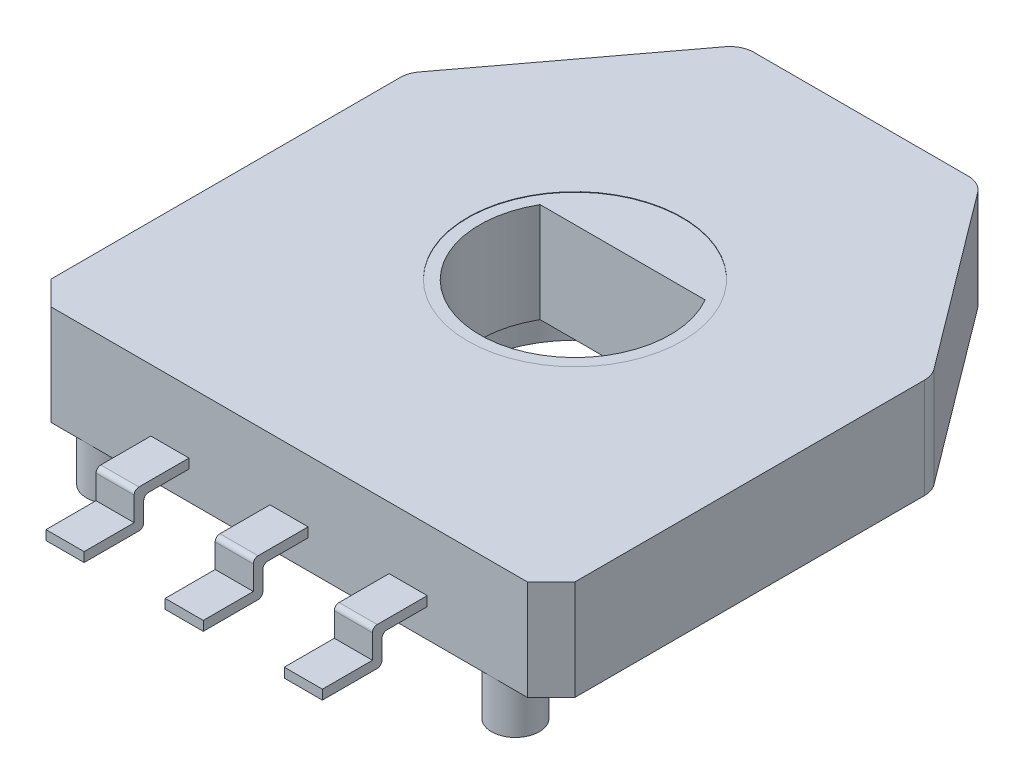
SolidWorks part; units mm, degrees
ref_plane "Front Plane" through (0, 0, 0) normal (0, 0, 1) x (1, 0, 0)
ref_plane "Top Plane" through (0, 0, 0) normal (0, 1, 0) x (1, 0, 0)
ref_plane "Right Plane" through (0, 0, 0) normal (1, 0, 0) x (0, 0, -1)
sketch "Sketch1" plane through (0, 0, 0) normal (0, 1, 0) x (1, 0, 0)
  line L0 (-1005.5, 0) -> (48994.5, 0) construction
  line L1 (5.5, -6) -> (-5.5, -6)
  line L2 (5.5, -6) -> (5.5, 6)
  line L3 (5.5, 6) -> (-5.5, 6)
  line L4 (-5.5, -6) -> (-5.5, 6)
  line L5 (5.5, -6) -> (-5.5, 6) construction
  line L6 (5.5, 6) -> (-5.5, -6) construction
  line L7 (0, -994) -> (0, 49006) construction
  line L8 (-1.7321, 1) -> (1.7321, 1)
  line L9 (-1005.5, 1) -> (48994.5, 1) construction
  line L10 (-1012.2378, 2) -> (48987.7622, 2) construction
  line L11 (2.5, -994) -> (2.5, 49006) construction
  line L12 (-2.5, -994) -> (-2.5, 49006) construction
  line L13 (-5.5, 2) -> (-2.5, 6)
  line L14 (2.5, 6) -> (5.5, 2)
  line L15 (-1005.5, -5.5) -> (48994.5, -5.5) construction
  line L16 (-5.5, -5.5) -> (-5, -6)
  line L17 (5.5, -5.5) -> (5, -6)
  arc A0 (-1.7321, 1) -> (1.7321, 1) centre (0, 0) ccw
  circle A1 centre (0, 0) radius 2.5
  point P0 (0, 0)
  point P9 (-5.5, 0)
  point P12 (0, 6)
  dimension "D3" = 4
  dimension "D5" = 5
  dimension "D1" = 11
  dimension "D2" = 12
  dimension "D6" = 2
  dimension "D10" = 0.5
  dimension "D4" = 1
  dimension "D7" = 2.5
  dimension "D8" = 2.5
  dimension "D9" = 5.5
extrude "FormaBase" add sketch "Sketch1" along normal blind 2.1 contours L17 L2 L14 L3 L13 L4 L16 L1 A1 | A1 A0 L8
fillet "Fillet1" radius 0.5 4 edges at (-2.5, 1.05, -6) (2.5, 1.05, -6) (5.5, 1.05, -2) (-5.5, 1.05, -2)
sketch "Sketch2" plane through (5.5, 0, 0) normal (1, 0, 0) x (0, 0, -1)
  line L0 (-1000, 0) -> (0, 0) construction
  line L1 (0, -1000) -> (0, 49000) construction
  line L2 (-7.05, 0) -> (-8.2, 0)
  line L3 (-6, 0) -> (-6, 0.8)
  line L4 (-6, 0.8) -> (-7.05, 0.8)
  line L5 (-8.2, 0) -> (-8.2, 0.2)
  line L6 (-6.85, 0.6) -> (-6, 0.6)
  line L7 (-6.95, 0.1) -> (-6.95, 0.5)
  line L8 (-7.15, 0.2) -> (-7.15, 0.7)
  line L9 (-8.2, 0.2) -> (-7.15, 0.2)
  line L10 (-7.15, -1000) -> (-7.15, 49000) construction
  line L11 (-6.95, -1000) -> (-6.95, 49000) construction
  line L12 (-1000, 0.6) -> (49000, 0.6) construction
  line L13 (-1000, 0.2) -> (49000, 0.2) construction
  line L14 (-6.95, 0.2) -> (-6, 0.2)
  line L15 (-1006, 0.8) -> (0, 0.8) construction
  line L16 (6, 0) -> (6, 0.8)
  line L17 (6, 2.1) -> (6, 0) construction
  line L18 (6.1, 0.2) -> (6.1, 0.8)
  line L19 (6, 0) -> (6.7, 0)
  line L20 (-1000, 0) -> (49000, 0) construction
  line L21 (6.1, 0.2) -> (6.7, 0.2)
  line L22 (6, 0.8) -> (6.7, 0.8)
  line L23 (6.7, 0) -> (6.7, 0.8)
  line L24 (6.7, -998.95) -> (6.7, 49001.05) construction
  line L25 (6.1, -998.95) -> (6.1, 49001.05) construction
  line L26 (6, -998.95) -> (6, 49001.05) construction
  line L27 (6, 0) -> (49000, 0) construction
  line L28 (6, 0.2) -> (49000, 0.2) construction
  arc A0 (-7.05, 0) -> (-6.95, 0.1) centre (-7.05, 0.1) ccw
  arc A1 (-6.85, 0.6) -> (-6.95, 0.5) centre (-6.85, 0.5) ccw
  arc A2 (-7.15, 0.7) -> (-7.05, 0.8) centre (-7.05, 0.7) cw
  point P31 (-7.15, 0.8)
  point P39 (6, 1.05)
  dimension "D1" = 0.1
  dimension "D2" = 0.6
  dimension "D3" = 6.95
  dimension "D4" = 0.6
  dimension "D5" = 0.2
  dimension "D6" = 0.2
  dimension "D7" = 0.1
  dimension "D8" = 0.2
  dimension "D9" = 0.7
extrude "Boss-Extrude2" add sketch "Sketch2" against normal blind 2.9 and the other way blind 2.9 from offset 5.5 contours L9 L5 L2 L7 L6 L3 L4 L8 | L19 L23 L21 L18 L22 L16 offset against normal yes
sketch "Sketch3" plane through (0, 2.1, 0) normal (0, 1, 0) x (1, 0, 0)
  line L0 (0, -1000) -> (0, 6.7) construction
  line L1 (0.4, -1000) -> (0.4, 6.7)
  line L2 (-0.4, -1000) -> (-0.4, 6.7)
  line L3 (-2.9, 6.7) -> (-0.4, 6.7)
  line L4 (-1002.9, -8.2) -> (-2.9, -8.2)
  line L5 (-1005, -6) -> (-2.9, -6)
  line L6 (-2.9, 6) -> (-0.4, 6)
  line L7 (2.25, 6) -> (-2.25, 6) construction
  line L8 (-2.9, 6.7) -> (-2.9, 6)
  line L9 (2.9, 6) -> (2.9, 6.7)
  line L10 (2.9, 6.1) -> (2.9, 6.7) construction
  line L11 (0.4, -1000) -> (0.4, 49000) construction
  line L12 (0, -1000) -> (0, 49000) construction
  line L13 (-0.4, -1000) -> (-0.4, 49000) construction
  line L14 (0.4, 6.7) -> (2.9, 6.7)
  line L15 (0.4, 6) -> (2.9, 6)
  line L16 (0.4, -6) -> (2.1, -6)
  line L17 (0.4, -8.2) -> (2.1, -8.2)
  line L18 (2.5, -1000) -> (2.5, 6) construction
  line L19 (-2.5, -1000) -> (-2.5, 6) construction
  line L20 (-2.1, -1000) -> (-2.1, 6)
  line L21 (2.9, -1000) -> (2.9, 6.7)
  line L22 (-2.9, -1000) -> (-2.9, 6.7)
  line L23 (2.1, -1000) -> (2.1, 6)
  line L24 (-2.1, -1000) -> (-2.1, 6.7) construction
  line L25 (-2.5, -1000) -> (-2.5, 6.7) construction
  line L26 (2.1, -1000) -> (2.1, 6.7) construction
  line L27 (2.5, -1000) -> (2.5, 6.7) construction
  line L28 (-2.1, -6) -> (-0.4, -6)
  line L29 (-2.1, -8.2) -> (-0.4, -8.2)
  line L30 (2.9, -6) -> (48995, -6)
  line L31 (2.9, -8.2) -> (48997.1, -8.2)
  point P21 (0, 6)
  line M1 (2.25, 6) -> (-2.25, 6)
  line M7 (-5, -6) -> (5, -6)
  dimension "D1" = 0.4
  dimension "D2" = 0.4
  dimension "D3" = 2.5
  dimension "D4" = 2.5
  dimension "D5" = 0.4
  dimension "D6" = 0.4
extrude "Cut-Extrude1" cut sketch "Sketch3" against normal through all contours L20 L29 L2 M7 | L17 L23 L1 M7 | L3 L8 L6 L2 M1 | L15 L9 L14 L1 M1
sketch "Sketch4" plane through (0, 0, 0) normal (0, -1, 0) x (1, 0, 0)
  line L0 (0, -994) -> (0, 49006) construction
  line L1 (0.4, 6) -> (-0.4, 6) construction
  line L2 (4.25, -994) -> (4.25, 49006) construction
  line L3 (-4.25, -994) -> (-4.25, 49006) construction
  line L4 (-1000, 0) -> (49000, 0) construction
  line L5 (-1000, 5.5) -> (49000, 5.5) construction
  circle A0 centre (0, 0) radius 2.25
  circle A1 centre (0, 0) radius 2.5
  circle A2 centre (4.25, 5.5) radius 0.5
  circle A3 centre (-4.25, 5.5) radius 0.5
  point P9 (0, 6)
  dimension "D1" = 4.5
  dimension "D2" = 5
  dimension "D6" = 1
  dimension "D7" = 1
  dimension "D3" = 4.25
  dimension "D4" = 4.25
  dimension "D5" = 5.5
extrude "Boss-Extrude3" add sketch "Sketch4" along normal blind 0.6
sketch "Sketch5" plane through (0, -0.6, 0) normal (0, -1, 0) x (1, 0, 0)
  circle A0 centre (-4.25, 5.5) radius 0.5
  circle A1 centre (4.25, 5.5) radius 0.5
  dimension "D1" = 1
  dimension "D2" = 1
extrude "Boss-Extrude4" add sketch "Sketch5" along normal blind 0.4
sketch "Sketch6" plane through (0, 2.1, 0) normal (0, 1, 0) x (1, 0, 0)
  circle A0 centre (0, 0) radius 2.25
  dimension "D1" = 4.5
extrude "Cut-Extrude2" cut sketch "Sketch6" against normal blind 0.01
